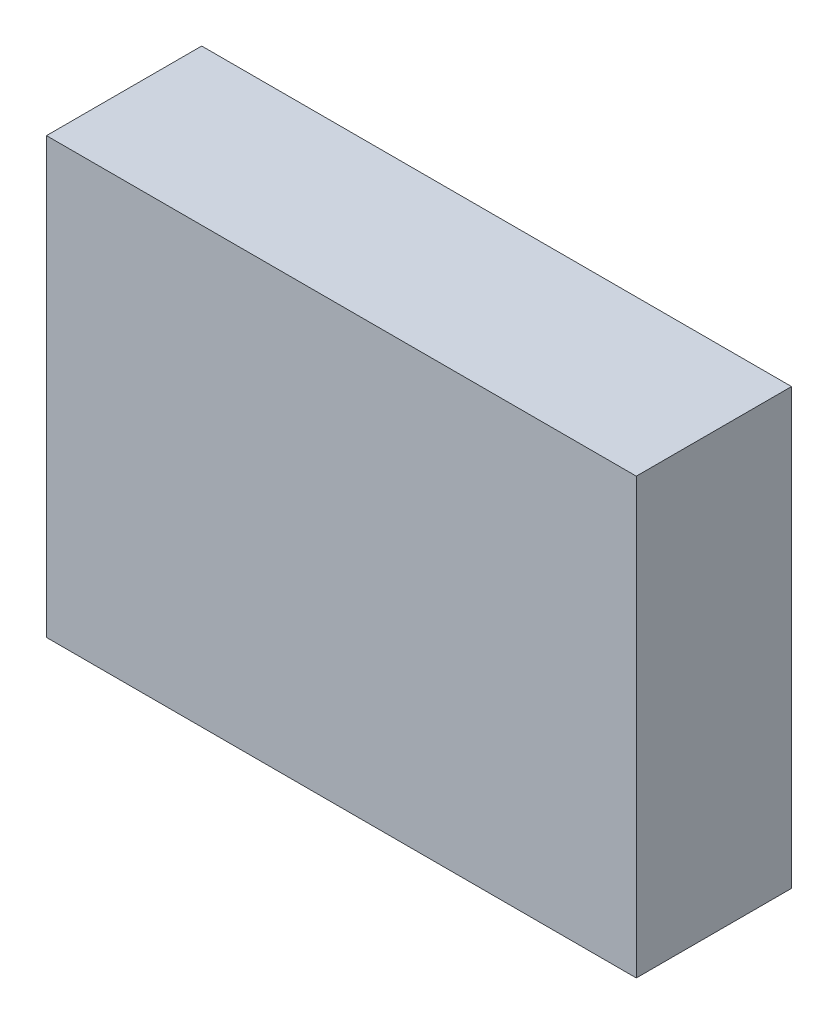
SolidWorks part; units mm, degrees
ref_plane "Front Plane" through (0, 0, 0) normal (0, 0, 1) x (1, 0, 0)
ref_plane "Top Plane" through (0, 0, 0) normal (0, 1, 0) x (1, 0, 0)
ref_plane "Right Plane" through (0, 0, 0) normal (1, 0, 0) x (0, 0, -1)
sketch "Sketch1" plane through (0, 0, 0) normal (0, 0, 1) x (1, 0, 0)
  line L1 (-95, -70) -> (95, -70)
  line L2 (-95, -70) -> (-95, 70)
  line L3 (-95, 70) -> (95, 70)
  line L4 (95, -70) -> (95, 70)
  line L5 (-95, -70) -> (95, 70) construction
  line L6 (-95, 70) -> (95, -70) construction
  point P0 (0, 0)
extrude "Boss-Extrude1" add sketch "Sketch1" along normal blind 50
